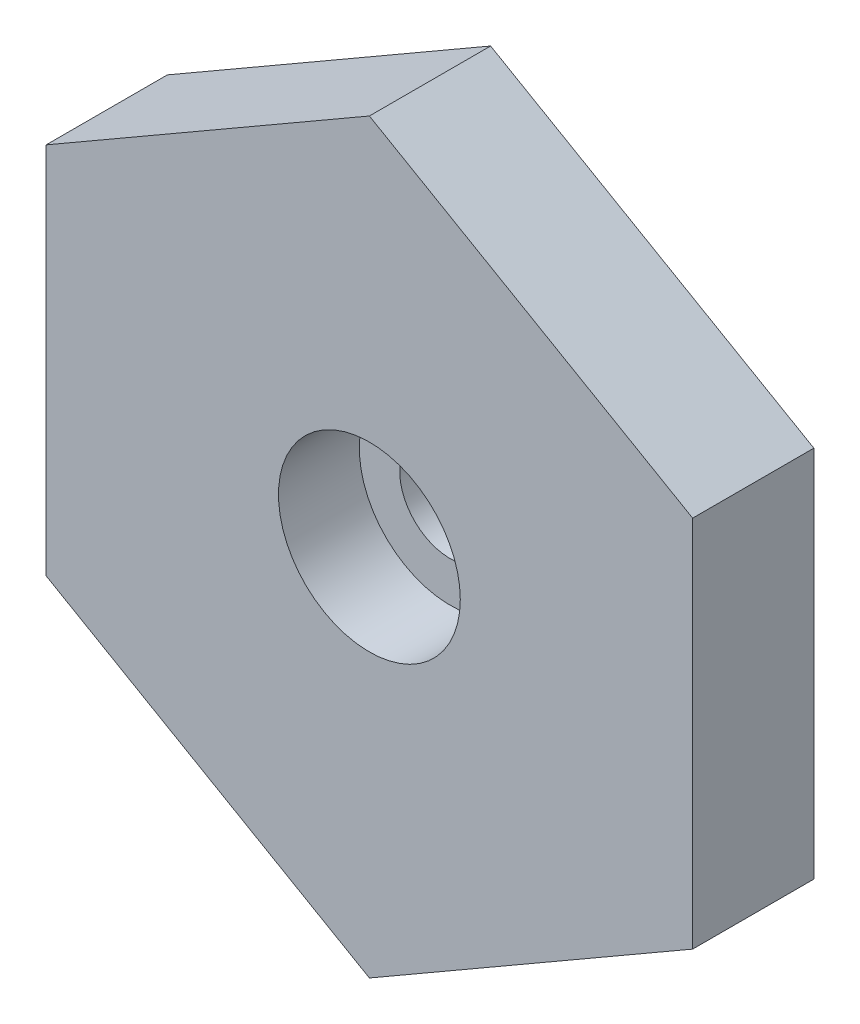
SolidWorks part; units mm, degrees
ref_plane "Ebene vorne" through (0, 0, 0) normal (0, 0, 1) x (1, 0, 0)
ref_plane "Ebene oben" through (0, 0, 0) normal (0, 1, 0) x (1, 0, 0)
ref_plane "Ebene rechts" through (0, 0, 0) normal (1, 0, 0) x (0, 0, -1)
sketch "Skizze1" plane through (0, 0, 0) normal (0, 0, 1) x (1, 0, 0)
  line L1 (16, 9.2376) -> (0, 18.4752)
  line L2 (0, 18.4752) -> (-16, 9.2376)
  line L3 (-16, 9.2376) -> (-16, -9.2376)
  line L4 (-16, -9.2376) -> (0, -18.4752)
  line L5 (0, -18.4752) -> (16, -9.2376)
  line L6 (16, -9.2376) -> (16, 9.2376)
  circle A0 centre (0, 0) radius 16 construction
  circle A1 centre (0, 0) radius 2.5
extrude "Aufsatz-Linear austragen1" add sketch "Skizze1" along normal blind 6
sketch "Skizze2" plane through (0, 0, 6) normal (0, 0, 1) x (1, 0, 0)
  circle A0 centre (0, 0) radius 4.5
extrude "Schnitt-Linear austragen1" cut sketch "Skizze2" against normal blind 4
sketch "Skizze3" plane through (0, 0, 0) normal (0, 0, -1) x (-1, 0, 0)
  line L1 (13.9719, 0) -> (6.9859, 12.1)
  line L2 (6.9859, 12.1) -> (-6.9859, 12.1)
  line L3 (-6.9859, 12.1) -> (-13.9719, 0)
  line L4 (-13.9719, 0) -> (-6.9859, -12.1)
  line L5 (-6.9859, -12.1) -> (6.9859, -12.1)
  line L6 (6.9859, -12.1) -> (13.9719, 0)
  circle A0 centre (0, 0) radius 12.1 construction
  circle A1 centre (0, 0) radius 8
extrude "Schnitt-Linear austragen2" cut sketch "Skizze3" against normal blind 4
